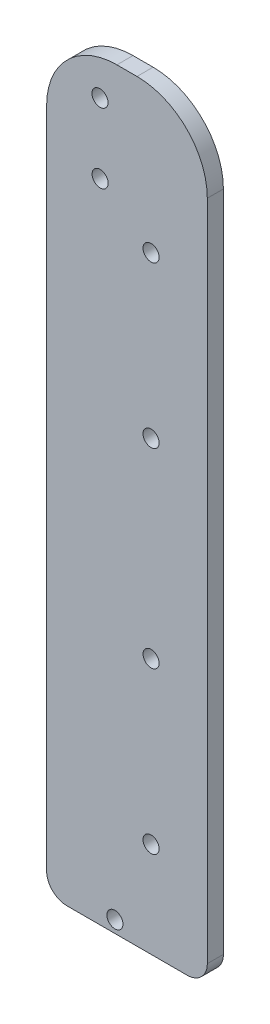
SolidWorks part; units mm, degrees
ref_plane "Front Plane" through (0, 0, 0) normal (0, 0, 1) x (1, 0, 0)
ref_plane "Top Plane" through (0, 0, 0) normal (0, 1, 0) x (1, 0, 0)
ref_plane "Right Plane" through (0, 0, 0) normal (1, 0, 0) x (0, 0, -1)
sketch "Sketch1" plane through (0, 0, 0) normal (0, 0, 1) x (1, 0, 0)
  line L1 (0, -146.6506) -> (0, 146.6506) construction
  line L3 (40.64, 5.08) -> (40.64, 172.72)
  line L5 (35.56, 0) -> (26.416, 0)
  line L7 (66.681, 0) -> (66.681, 88.9) construction
  line L8 (26.416, 0) -> (40.64, 0) construction
  line L9 (26.416, 177.8) -> (26.416, 0) construction
  line L10 (118.1346, 0) -> (-118.1346, 0) construction
  line L11 (66.681, 88.9) -> (0, 88.9) construction
  line L14 (26.416, 0) -> (5.08, 0)
  line L18 (66.681, 88.9) -> (66.681, 177.8) construction
  line L19 (66.681, 177.8) -> (0, 177.8) construction
  line L20 (0, 5.08) -> (0, 172.72)
  line L23 (26.416, 0) -> (20.32, 0) construction
  line L24 (20.32, 0) -> (19.8425, 177.8) construction
  line L25 (20.32, 0) -> (14.732, 0) construction
  line L26 (14.732, 0) -> (14.732, 8.89) construction
  line L27 (14.732, 8.89) -> (14.732, 177.8) construction
  line L28 (26.416, 24.13) -> (0, 24.13) construction
  line L35 (20.32, 0) -> (17.6513, 0) construction
  line L36 (17.6513, 0) -> (17.6513, 177.8) construction
  line L46 (17.78, 190.5) -> (22.86, 190.5)
  line L47 (19.8425, 177.8) -> (19.8425, 190.5) construction
  line L48 (19.8896, 160.274) -> (19.8425, 190.5) construction
  line L49 (19.8425, 190.5) -> (-14.4304, 190.5) construction
  line L50 (19.8896, 160.274) -> (0, 160.274) construction
  circle A0 centre (26.416, 24.13) radius 2.032
  circle A1 centre (26.416, 64.77) radius 2.032
  arc A5 (35.56, 0) -> (40.64, 5.08) centre (35.56, 5.08) ccw
  arc A6 (5.08, 0) -> (0, 5.08) centre (5.08, 5.08) cw
  circle A7 centre (26.416, 113.03) radius 2.032
  circle A8 centre (26.416, 153.67) radius 2.032
  arc A13 (40.64, 172.72) -> (22.86, 190.5) centre (22.86, 172.72) ccw
  arc A14 (0, 172.72) -> (17.78, 190.5) centre (17.78, 172.72) cw
  circle A15 centre (17.272, 3.048) radius 2.032
  circle A17 centre (13.531, 163.449) radius 2.032
  circle A20 centre (13.4925, 181.102) radius 2.032
  point P24 (0, 190.5)
  point P30 (0, 0)
  point P38 (0, 190.5)
  point P42 (0, 185.42)
  point P46 (40.64, 185.0608)
  point P52 (0, 190.5)
  dimension "D7" = 4.064
  dimension "D5" = 24.13
  dimension "D6" = 4.064
  dimension "D9" = 24.13
  dimension "D11" = 88.9
  dimension "D12" = 5.08
  dimension "D13" = 4.064
  dimension "D15" = 4.064
  dimension "D17" = 4.064
  dimension "D19" = 17.78
  dimension "D22" = 4.064
  dimension "D26" = 4.064
  dimension "D20" = 23.368
  dimension "D27" = 6.35
  dimension "D29" = 6.35
  dimension "D1" = 190.5
  dimension "D2" = 40.64
  dimension "D3" = 88.9
  dimension "D4" = 14.224
  dimension "D8" = 40.64
  dimension "D10" = 24.13
  dimension "D14" = 3.048
  dimension "D16" = 40.64
  dimension "D18" = 24.13
  dimension "D21" = 30.226
  dimension "D23" = 20.32
  dimension "D24" = 25.908
  dimension "D28" = 64.77
  dimension "D32" = 2.6687
extrude "Boss-Extrude2" add sketch "Sketch1" along normal blind 4.064
